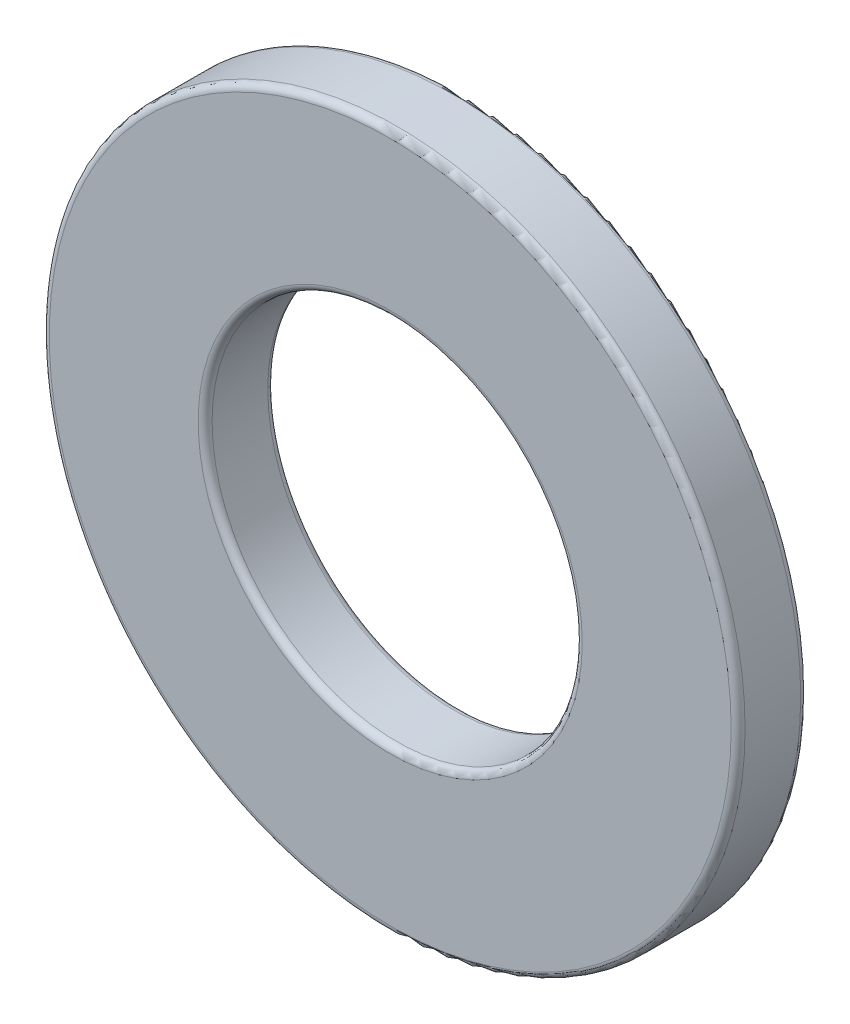
SolidWorks part; units mm, degrees
material "Stainless Steel (ferritic)"
ref_plane "Front Plane" through (0, 0, 0) normal (0, 0, 1) x (1, 0, 0)
ref_plane "Top Plane" through (0, 0, 0) normal (0, 1, 0) x (1, 0, 0)
ref_plane "Right Plane" through (0, 0, 0) normal (1, 0, 0) x (0, 0, -1)
sketch "Sketch1" plane through (0, 0, 0) normal (0, 0, 1) x (1, 0, 0)
  circle A0 centre (0, 0) radius 3.3782
  circle A1 centre (0, 0) radius 6.35
  point P4 (0, 6.35)
  point P5 (0, 3.3782)
  point P6 (0, -3.3782)
  point P7 (3.3782, 0)
  point P8 (-3.3782, 0)
  dimension "OD" = 12.7
  dimension "ID" = 6.7564
sketch "Sketch2" plane through (0, 0, 0) normal (1, 0, 0) x (0, 0, -1)
  line L1 (-0.635, 6.35) -> (0.635, 6.35)
  line L2 (-0.635, 6.35) -> (-0.635, -6.35)
  line L3 (-0.635, -6.35) -> (0.635, -6.35)
  line L4 (0.635, 6.35) -> (0.635, -6.35)
  point P4 (0, 6.35)
  point P5 (0.635, 0)
  dimension "Thickness" = 1.27
sketch "Sketch3" plane through (0, 0, 0) normal (0, 0, 1) x (1, 0, 0)
  circle A0 centre (0, 0) radius 3.3782 construction
  circle A1 centre (0, 0) radius 6.35 construction
  circle A2 centre (0, 0) radius 3.3782
  circle A3 centre (0, 0) radius 6.35
extrude "Boss-Extrude1" add sketch "Sketch3" against normal up to vertex (0.635 mm away) from vertex at 0.635 starting at point (0, 6.35, 0.635)
fillet "Fillet1" radius 0.127 4 edges at (3.3782, 0, 0.635) (3.3782, 0, -0.635) (6.35, 0, 0.635) (6.35, 0, -0.635)
equation "\"D1@Fillet1\"=\"Thickness@Sketch2\"*.1"
